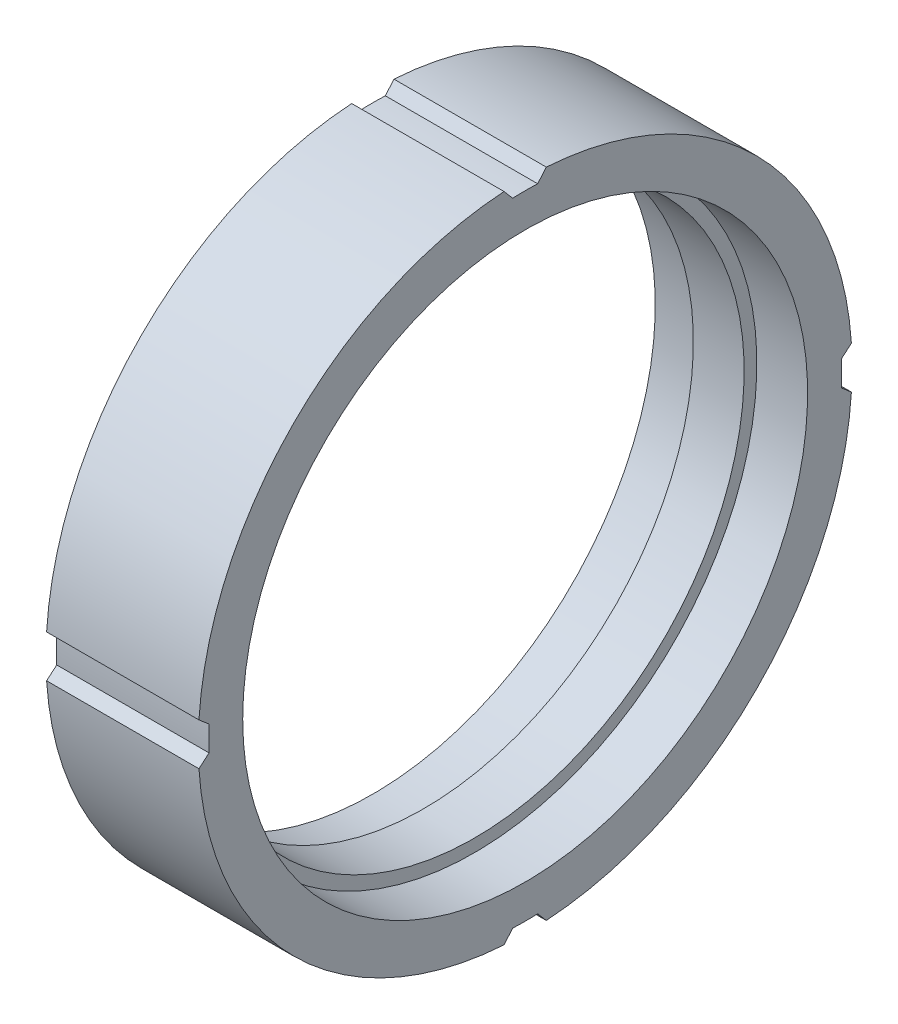
SolidWorks part; units mm, degrees
ref_plane "Plano frontal" through (0, 0, 0) normal (0, 0, 1) x (1, 0, 0)
ref_plane "Plano superior" through (0, 0, 0) normal (0, 1, 0) x (1, 0, 0)
ref_plane "Plano direito" through (0, 0, 0) normal (1, 0, 0) x (0, 0, -1)
sketch "Esboço4" plane through (0, 0, 0) normal (0, 0, -1) x (0, 1, 0)
  line L0 (0, -0.6225) -> (0, 3.4419) construction
  line L1 (-5.15, -0.117) -> (-5.15, 2.283)
  line L2 (-5.15, 2.283) -> (-4.45, 2.283)
  line L3 (-4.45, 2.283) -> (-4.45, 1.483)
  line L4 (-4.45, 1.483) -> (-4.25, 1.483)
  line L5 (-4.25, 1.483) -> (-4.25, 0.683)
  line L6 (-4.25, 0.683) -> (-4.45, 0.683)
  line L7 (-4.45, 0.683) -> (-4.45, -0.117)
  line L8 (-4.45, -0.117) -> (-5.15, -0.117)
  line L9 (-5.15, 1.083) -> (-4.25, 1.083) construction
  dimension "D1" = 8.5
  dimension "D2" = 10.3
  dimension "D3" = 2.4
  dimension "D4" = 0.8
  dimension "D5" = 0.8
  dimension "D6" = 0.8
  dimension "D7" = 0.7
  dimension "D8" = 2.283
revolve "Revolução1" add sketch "Esboço4" angle 360 about L0
sketch "Esboço5" plane through (2.283, 0, 0) normal (1, 0, 0) x (0, 0, 1)
  line L0 (0, 4.9837) -> (0, 5.125) construction
  line L1 (-0.1968, 4.9799) -> (-0.3329, 5.1392)
  line L2 (0.1968, 4.9799) -> (0.3329, 5.1392)
  arc A0 (0.1968, 4.9799) -> (-0.1968, 4.9799) centre (0, 0) ccw
  circle A1 centre (0, 0) radius 5.15 construction
  circle A3 centre (0, 0) radius 5.15
  arc A4 (0.3329, 5.1392) -> (-0.3329, 5.1392) centre (0, 0) ccw
  dimension "D1" = 0
extrude "Extrusão4" cut sketch "Esboço5" against normal through all
pattern_circular "PadrãoCircular2" count 4 over 360 about axis through (0, 0, 0) along (1, 0, 0) of "Extrusão4"
